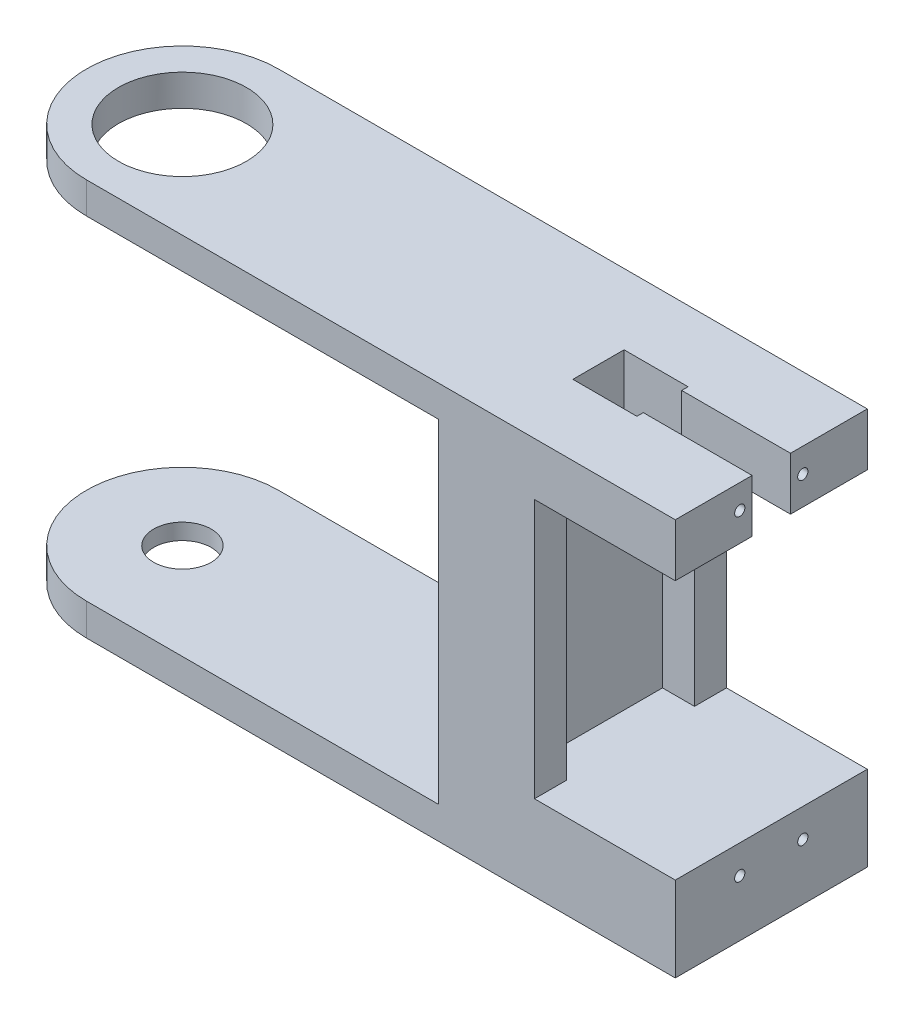
SolidWorks part; units mm, degrees
other "Marquage1"
sketch "Esquisse9" plane through (30.25, -27, 30) normal (0.9363, -0.2766, 0.2166) x (0.221, -0.0157, -0.9752)
sketch "Esquisse35" plane through (11.75, 27, 30) normal (0.9363, -0.2766, 0.2166) x (0.221, -0.0157, -0.9752)
ref_plane "Plan de face" through (0, 0, 0) normal (0, 0, 1) x (1, 0, 0)
ref_plane "Plan de dessus" through (0, 0, 0) normal (0, 1, 0) x (1, 0, 0)
ref_plane "Plan de droite" through (0, 0, 0) normal (1, 0, 0) x (0, 0, -1)
sketch "Esquisse1" plane through (0, 0, 0) normal (0, 0, 1) x (1, 0, 0)
  line L1 (-30.25, 32) -> (30.25, 32)
  line L2 (-30.25, 32) -> (-30.25, -32)
  line L3 (-30.25, -32) -> (30.25, -32)
  line L4 (30.25, 32) -> (30.25, -32)
  line L5 (-30.25, 32) -> (30.25, -32) construction
  line L6 (-30.25, -32) -> (30.25, 32) construction
  point P0 (0, 0)
  dimension "D1" = 60.5
  dimension "D2" = 64
extrude "Boss.-Extru.1" add sketch "Esquisse1" along normal blind 30
sketch "Esquisse2" plane through (30.25, 0, 0) normal (1, 0, 0) x (0, 0, -1)
  line L0 (-15, 32) -> (-15, -32) construction
  line L1 (-30, 32) -> (0, 32) construction
  line L2 (-30, -32) -> (0, -32) construction
  circle A0 centre (-15, -17) radius 4.5
  point P8 (-15, -17)
  dimension "D1" = 15
  dimension "D2" = 9
extrude "Enlèv. mat.-Extru.1" cut sketch "Esquisse2" against normal blind 32
sketch "Esquisse4" plane through (0, 0, 30) normal (0, 0, 1) x (1, 0, 0)
  line L0 (0, 0) -> (0, -11.7818) construction
  line L1 (-25.55, -56.5577) -> (25.55, -56.5577)
  line L2 (-25.55, -56.5577) -> (-25.55, 27)
  line L3 (-25.55, 27) -> (25.55, 27)
  line L4 (25.55, -56.5577) -> (25.55, 27)
  line L5 (30.25, 32) -> (-30.25, 32) construction
  dimension "D1" = 51.1
  dimension "D2" = 5
extrude "Enlèv. mat.-Extru.2" cut sketch "Esquisse4" against normal up to surface (30 mm away) up to face at (0, 0, 0)
sketch "Esquisse5" plane through (30.25, 0, 0) normal (1, 0, 0) x (0, 0, -1)
  circle A0 centre (-15, -17) radius 10.5
  dimension "D1" = 21
extrude "Enlèv. mat.-Extru.3" cut sketch "Esquisse5" against normal blind 2
sketch "Esquisse6" plane through (-25.55, 0, 0) normal (1, 0, 0) x (0, 0, -1)
  circle A0 centre (-15, -17) radius 10
extrude "Enlèv. mat.-Extru.4" cut sketch "Esquisse6" against normal up to surface (4.7 mm away) up to face at (-30.25, 0, 15)
sketch "Esquisse7" plane through (0, 0, 30) normal (0, 0, 1) x (1, 0, 0)
  line L0 (0, 0) -> (0, 32.5445) construction
  line L2 (-30.25, 32) -> (16.75, 32)
  line L3 (-30.25, 32) -> (-30.25, 89)
  line L4 (-30.25, 89) -> (16.75, 89)
  line L5 (16.75, 32) -> (16.75, 89)
  dimension "D1" = 57
  dimension "D2" = 47
extrude "Boss.-Extru.2" add sketch "Esquisse7" against normal up to surface (30 mm away) up to face at (0, -1.25, 0)
sketch "Esquisse8" plane through (0, 0, 30) normal (0, 0, 1) x (1, 0, 0)
  line L0 (-15.25, 90.392) -> (-15.25, 19.4965) construction
  line L1 (-30.25, 89) -> (-30.25, -32) construction
  line L2 (16.75, 60.5) -> (-55.9253, 60.5) construction
  line L3 (16.75, 32) -> (16.75, 89) construction
  line L4 (30.25, 32) -> (16.75, 32) construction
  line L6 (-15.25, 80.75) -> (11.75, 80.75)
  line L7 (-15.25, 80.75) -> (-15.25, 40.25)
  line L8 (-15.25, 40.25) -> (11.75, 40.25)
  line L10 (11.75, 40.25) -> (11.75, 32)
  line L11 (11.75, 101.1498) -> (21.75, 101.1498)
  line L12 (11.75, 101.1498) -> (11.75, 80.75)
  line L13 (11.75, 32) -> (21.75, 32)
  line L14 (21.75, 101.1498) -> (21.75, 32)
  dimension "D1" = 15
  dimension "D2" = 28.5
  dimension "D3" = 28.5
  dimension "D4" = 40.5
  dimension "D5" = 27
  dimension "D6" = 10
extrude "Enlèv. mat.-Extru.5" cut sketch "Esquisse8" against normal up to surface (30 mm away) up to face at (3.35, 16.8, 0)
sketch "Esquisse10" plane through (0, 80.75, 0) normal (0, -1, 0) x (1, 0, 0)
  line L0 (-1.75, 30) -> (-1.75, -1.0034) construction
  line L1 (-15.25, 15) -> (11.75, 15) construction
  line L2 (5.75, 0) -> (11.75, 0) construction
  line L4 (-15.25, 0) -> (11.75, 0)
  line L5 (11.75, 0) -> (11.75, 30)
  line L6 (11.75, 30) -> (-15.25, 30)
  line L7 (-15.25, 30) -> (-15.25, 0)
  line L8 (-15.25, 0) -> (-9.25, 0) construction
  line L9 (11.75, 0) -> (11.75, 30) construction
  line L10 (11.75, 30) -> (-15.25, 30) construction
  line L11 (-15.25, 30) -> (-15.25, 0) construction
  line L15 (-5.25, 11) -> (-5.25, 12)
  line L16 (-15.25, 19) -> (-5.25, 19)
  line L17 (-15.25, 19) -> (-15.25, 11)
  line L18 (-15.25, 11) -> (-5.25, 11)
  line L19 (34.75, 18) -> (34.75, 12)
  line L21 (-5.25, 19) -> (-5.25, 18)
  line L22 (-5.25, 18) -> (34.75, 18)
  line L24 (-5.25, 12) -> (34.75, 12)
  dimension "D2" = 6
  dimension "D4" = 10
  dimension "D1" = 0
extrude "Enlèv. mat.-Extru.6" cut sketch "Esquisse10" against normal up to surface (8.25 mm away) contours L17 L18 L15 L24 L19 L22 L21 L16 up to face at (-9.25, 89, 15)
sketch "Esquisse11" plane through (-15.25, 0, 0) normal (1, 0, 0) x (0, 0, -1)
  line L0 (-15, 103.0984) -> (-15, 64.9016) construction
  line L2 (0, 40.25) -> (-30, 40.25) construction
  line L3 (-30, 80.75) -> (-25, 80.75)
  line L4 (-30, 80.75) -> (-30, 40.25)
  line L5 (-30, 40.25) -> (-25, 40.25)
  line L6 (-25, 80.75) -> (-25, 40.25)
  line L7 (0, 40.25) -> (-5, 40.25)
  line L8 (-5, 80.75) -> (-5, 40.25)
  line L9 (0, 80.75) -> (-5, 80.75)
  line L10 (0, 80.75) -> (0, 40.25)
  point P3 (-15, 84)
  dimension "D1" = 5
extrude "Boss.-Extru.3" add sketch "Esquisse11" along normal blind 5
sketch "Esquisse12" plane through (11.75, 0, 0) normal (1, 0, 0) x (0, 0, -1)
  line L0 (-15, 89) -> (-15, 40.25) construction
  line L1 (-19, 89) -> (-11, 89) construction
  line L2 (0, 40.25) -> (-30, 40.25) construction
  line L3 (0, 80.75) -> (-12, 80.75) construction
  line L4 (-25, 60.5) -> (3.7732, 60.5) construction
  line L5 (-25, 40.25) -> (-25, 80.75) construction
  circle A0 centre (-19.925, 85.21) radius 0.5
  circle A1 centre (-10.075, 85.21) radius 0.5
  circle A2 centre (-10.075, 35.79) radius 0.5
  circle A3 centre (-19.925, 35.79) radius 0.5
  point P6 (-10.075, 85.21)
  point P9 (-19.925, 35.79)
  point P10 (-19.925, 85.21)
  point P15 (-10.075, 35.79)
  dimension "D3" = 1
  dimension "D1" = 4.46
  dimension "D2" = 4.925
  dimension "D4" = 4.925
  dimension "D5" = 4.46
extrude "Enlèv. mat.-Extru.7" cut sketch "Esquisse12" against normal blind 15
hole_wizard "Trou taraudé M2x0.42" positions "Esquisse3D2" profile "Esquisse14" tap size "M2x0.4" standard "Ansi Metric"
sketch3d "Esquisse3D2"
  line L0 (-3.25, 85.21, 19.925) -> (11.75, 85.21, 19.925) construction
  line L1 (-3.25, 85.21, 10.075) -> (11.75, 85.21, 10.075) construction
  line L2 (-3.25, 35.79, 10.075) -> (11.75, 35.79, 10.075) construction
  line L3 (-3.25, 35.79, 19.925) -> (11.75, 35.79, 19.925) construction
  point P0 (11.75, 85.21, 19.925)
  point P4 (11.75, 85.21, 10.075)
  point P8 (11.75, 35.79, 10.075)
  point P12 (11.75, 35.79, 19.925)
cosmetic thread "Filetage de perçage5" parameters "D1"=15, "D2"=2
cosmetic thread "Filetage de perçage6" parameters "D1"=15, "D2"=2
cosmetic thread "Filetage de perçage7" parameters "D1"=15, "D2"=2
cosmetic thread "Filetage de perçage8" parameters "D1"=15, "D2"=2
sketch "Esquisse14" plane through (11.75, 85.21, 19.925) normal (0, 1, 0) x (0, 0, -1)
  line L0 (0, 0) -> (0, 17.4807)
  line L1 (0, 17.4807) -> (0.8, 17)
  line L2 (0.8, 17) -> (0.8, 0)
  line L5 (0.8, 0) -> (0, 0)
  line L10 (0, 17.4807) -> (-0.8, 17) construction
  line L11 (0, -6.35) -> (0, 107.95) construction
  dimension "Diamètre du trou pour taraudage" = 1.6
  dimension "Profondeur du trou pour taraudage" = 17
  dimension "Angle de pointe" = 118
sketch "Esquisse15" plane through (-30.25, 0, 0) normal (-1, 0, 0) x (0, 0, 1)
  line L0 (30, -32) -> (0, -32) construction
  line L1 (40, -17) -> (30, -17)
  line L2 (0, -17) -> (-10, -17)
  arc A0 (5, -17) -> (25, -17) centre (15, -17) ccw construction
  arc A1 (0, -17) -> (30, -17) centre (15, -17) ccw
  arc A2 (-10, -17) -> (40, -17) centre (15, -17) ccw
  dimension "D1" = 20
  dimension "D2" = 50
extrude "Enlèv. mat.-Extru.8" cut sketch "Esquisse15" against normal up to surface (60.5 mm away) up to face at (30.25, -6.5, 15)
sketch "Esquisse17" plane through (-15.25, 0, 0) normal (1, 0, 0) x (0, 0, -1)
  line L0 (-15, 89) -> (-15, 40.25) construction
  line L1 (-19, 89) -> (-11, 89) construction
  line L2 (0, 40.25) -> (-30, 40.25) construction
  line L3 (-5, 70.15) -> (-34.9076, 70.15) construction
  line L4 (-5, 80.75) -> (-5, 40.25) construction
  line L5 (-25, 40.25) -> (-25, 80.75) construction
  line L6 (-5, 40.25) -> (-25, 40.25) construction
  circle A0 centre (-15, 70.15) radius 9.25
  point P14 (-15, 70.15)
  dimension "D1" = 10
  dimension "D2" = 29.9
sketch "Esquisse21" plane through (-30.25, 0, 0) normal (-1, 0, 0) x (0, 0, 1)
  circle A0 centre (15, 70.15) radius 9.25 construction
  circle A1 centre (15, 70.15) radius 9.25 construction
  circle A2 centre (15, 70.15) radius 1
  point P4 (15, 70.15)
sketch "Esquisse22" plane through (0, 0, 30) normal (0, 0, 1) x (1, 0, 0)
  line L0 (25.55, 27) -> (-25.55, 27) construction
  line L1 (39.5686, -40.8758) -> (-43.4034, -40.8758)
  line L2 (39.5686, -40.8758) -> (39.5686, 27)
  line L3 (39.5686, 27) -> (-43.4034, 27)
  line L4 (-43.4034, -40.8758) -> (-43.4034, 27)
extrude "Enlèv. mat.-Extru.10" cut sketch "Esquisse22" against normal up to surface (30 mm away) up to face at (1.8929, 33.5714, 0)
sketch "Esquisse23" plane through (0, 0, 0) normal (0, 0, -1) x (-1, 0, 0)
  line L0 (30.25, 58) -> (46.9038, 58) construction
  line L1 (30.25, 89) -> (30.25, 27) construction
  line L2 (30.25, 32) -> (85.25, 32)
  line L3 (30.25, 89) -> (85.25, 89)
  line L4 (30.25, 89) -> (30.25, 84.1)
  line L5 (30.25, 84.1) -> (85.25, 84.1)
  line L6 (85.25, 89) -> (85.25, 84.1)
  line L7 (85.25, 27) -> (85.25, 32)
  line L8 (30.25, 27) -> (85.25, 27)
  line L9 (30.25, 27) -> (30.25, 32)
  line L10 (30.25, 27) -> (-30.25, 27) construction
  dimension "D1" = 4.9
  dimension "D2" = 55
  dimension "D3" = 5
  dimension "D4" = 52.1
extrude "Boss.-Extru.4" add sketch "Esquisse23" against normal up to surface (30 mm away) up to face at (2.65, 53.8, 30)
sketch "Esquisse24" plane through (0, 27, 0) normal (0, -1, 0) x (1, 0, 0)
  line L0 (-85.25, 15) -> (-94.2291, 15) construction
  line L2 (-74.25, 35) -> (-74.25, -10.9716) construction
  line L3 (-30.25, 30) -> (-30.25, 0) construction
  line L4 (-30.25, 30) -> (-30.25, 0)
  circle A0 centre (-74.25, 15) radius 10
  dimension "D1" = 20
  dimension "D2" = 44
extrude "Enlèv. mat.-Extru.11" cut sketch "Esquisse24" against normal up to surface (62 mm away) contours A0
sketch "Esquisse25" plane through (0, 27, 0) normal (0, -1, 0) x (1, 0, 0)
  line L0 (30.25, 30) -> (-85.25, 30) construction
  line L1 (-85.25, 0) -> (30.25, 0) construction
  line L2 (-74.25, 44.1348) -> (-74.25, 30)
  line L3 (-74.25, 0) -> (-74.25, -14.1348)
  arc A0 (-74.25, 30) -> (-74.25, 0) centre (-74.25, 15) ccw
  arc A1 (-74.25, 44.1348) -> (-74.25, -14.1348) centre (-74.25, 15) ccw
extrude "Enlèv. mat.-Extru.12" cut sketch "Esquisse25" against normal up to surface (62 mm away) up to face at (-74.25, 89, 25)
sketch "Esquisse26" plane through (0, 27, 0) normal (0, -1, 0) x (1, 0, 0)
  circle A0 centre (-74.25, 15) radius 4.5
  circle A1 centre (-74.25, 15) radius 10.5
extrude "Boss.-Extru.5" add sketch "Esquisse26" against normal up to surface (5 mm away) up to face at (-74.25, 32, 25)
sketch "Esquisse27" plane through (0, 27, 0) normal (0, -1, 0) x (1, 0, 0)
  circle A0 centre (-74.25, 15) radius 10.5
extrude "Enlèv. mat.-Extru.13" cut sketch "Esquisse27" against normal offset from surface (2.5 mm away) 2.5 up to face at (-63.4171, 32, 15)
sketch "Esquisse28" plane through (0, 32, 0) normal (0, 1, 0) x (1, 0, 0)
  line L1 (11.75, 0) -> (33.2878, 0)
  line L2 (11.75, 0) -> (11.75, -33.2244)
  line L3 (11.75, -33.2244) -> (33.2878, -33.2244)
  line L4 (33.2878, 0) -> (33.2878, -33.2244)
extrude "Enlèv. mat.-Extru.14" cut sketch "Esquisse28" against normal up to surface (5 mm away) up to face at (-63.75, 27, 15)
sketch "Esquisse29" plane through (0, 0, 0) normal (0, 0, -1) x (-1, 0, 0)
  line L0 (74.25, 32) -> (30.25, 32) construction
  line L1 (30.25, 84.1) -> (25.25, 84.1)
  line L2 (30.25, 84.1) -> (30.25, 32)
  line L3 (30.25, 32) -> (25.25, 32)
  line L4 (25.25, 84.1) -> (25.25, 32)
  dimension "D1" = 5
extrude "Enlèv. mat.-Extru.15" cut sketch "Esquisse29" against normal up to surface (30 mm away) up to face at (-27.5833, 58.85, 30)
sketch "Esquisse31" plane through (0, 27, 0) normal (0, -1, 0) x (1, 0, 0)
  line L0 (-82.4117, 21.6059) -> (-85.25, 25.198)
  line L1 (-74.25, 4.5) -> (-85.25, 4.802)
  arc A0 (-85.25, 25.198) -> (-85.25, 4.802) centre (-74.25, 15) ccw
  arc A1 (-85.25, 4.802) -> (-74.25, 0) centre (-74.25, 15) ccw construction
  arc A2 (-82.4117, 21.6059) -> (-74.25, 4.5) centre (-74.25, 15) ccw
  circle A3 centre (-74.25, 15) radius 10.5 construction
  circle M1 centre (-74.25, 15) radius 10.5
  line M6 (-85.25, 25.198) -> (-85.25, 4.802)
extrude "Boss.-Extru.6" add sketch "Esquisse31" against normal up to surface (62 mm away) contours L1 L0 M1 M6 | A0 M6 up to face at (-74.25, 89, 25)
sketch "Esquisse32" plane through (0.0675, 0, 2.4599) normal (-0.0274, 0, -0.9996) x (-0.9996, 0, 0.0274)
  line L0 (85.3497, 32) -> (74.222, 32) construction
  line L1 (74.9218, 84.1) -> (113.711, 84.1)
  line L2 (74.9218, 84.1) -> (74.9218, 32)
  line L3 (74.9218, 32) -> (113.711, 32)
  line L4 (113.711, 84.1) -> (113.711, 32)
extrude "Enlèv. mat.-Extru.16" cut sketch "Esquisse32" against normal up to surface (24.429 mm away)
sketch "Esquisse33" plane through (0, 32, 0) normal (0, 1, 0) x (1, 0, 0)
  line L3 (-74.25, -30) -> (-25.25, -30)
  line L4 (-25.25, -30) -> (-25.25, 0)
  line L5 (-25.25, 0) -> (-74.25, 0)
  line L6 (-74.25, -30) -> (-25.25, -30)
  line L7 (-25.25, -30) -> (-25.25, 0)
  line L8 (-25.25, 0) -> (-74.25, 0)
  arc A1 (-74.25, 0) -> (-74.25, -30) centre (-74.25, -15) ccw
  arc A2 (-74.25, 0) -> (-74.25, -30) centre (-74.25, -15) ccw
  dimension "D1" = 0
extrude "Boss.-Extru.7" [suppressed] add sketch "Esquisse33" along normal blind 0.4
sketch "Esquisse34" [suppressed] plane through (0, 32, 0) normal (0, -1, 0) x (1, 0, 0)
  circle A0 centre (-74.25, 15) radius 4.5
extrude "Enlèv. mat.-Extru.17" [suppressed] cut sketch "Esquisse34" against normal up to surface (0.4 mm away)
sketch "Esquisse36" plane through (0, 27, 0) normal (0, -1, 0) x (1, 0, 0)
  line L3 (-96.1298, 39.4832) -> (-25.25, 39.4832)
  line L4 (-96.1298, 39.4832) -> (-96.1298, -4.8162)
  line L5 (-96.1298, -4.8162) -> (-25.25, -4.8162)
  line L6 (-25.25, 39.4832) -> (-25.25, -4.8162)
extrude "Enlèv. mat.-Extru.20" cut sketch "Esquisse36" against normal up to surface (62 mm away) contours L4 L3 L6 L5 up to face at (-14, 89, 15)
sketch "Esquisse37" plane through (-25.25, 0, 0) normal (-1, 0, 0) x (0, 0, 1)
  line L0 (30, 89) -> (30, 27) construction
  line L1 (0, 89) -> (30, 89)
  line L2 (0, 89) -> (0, 84.1)
  line L3 (0, 84.1) -> (30, 84.1)
  line L4 (30, 89) -> (30, 84.1)
  line L6 (0, 27) -> (30, 27)
  line L7 (0, 27) -> (0, 32)
  line L8 (0, 32) -> (30, 32)
  line L9 (30, 27) -> (30, 32)
  dimension "D1" = 4.9
  dimension "D2" = 5
  dimension "D3" = 52.1
extrude "Boss.-Extru.8" add sketch "Esquisse37" along normal blind 70
sketch "Esquisse38" plane through (0, 27, 0) normal (0, -1, 0) x (1, 0, 0)
  line L0 (-95.25, 15) -> (-54.6175, 15) construction
  line L1 (-95.25, 0) -> (-95.25, 30) construction
  circle A0 centre (-80.25, 15) radius 4.5
  dimension "D1" = 15
extrude "Enlèv. mat.-Extru.21" cut sketch "Esquisse38" against normal up to surface (62 mm away) up to face at (-16.25, 89, 15)
sketch "Esquisse39" plane through (0, 89, 0) normal (0, 1, 0) x (1, 0, 0)
  circle A0 centre (-80.25, -15) radius 10
extrude "Enlèv. mat.-Extru.22" cut sketch "Esquisse39" against normal up to surface (4.9 mm away) up to face at (-84.75, 84.1, 15)
sketch "Esquisse40" plane through (0, 27, 0) normal (0, -1, 0) x (1, 0, 0)
  circle A0 centre (-80.25, 15) radius 10.5
extrude "Enlèv. mat.-Extru.23" cut sketch "Esquisse40" against normal offset from surface (2.5 mm away) 2.5 up to face at (-75.75, 32, 15)
sketch "Esquisse42" plane through (0, 27, 0) normal (0, -1, 0) x (1, 0, 0)
  line L0 (11.75, 30) -> (-95.25, 30) construction
  line L1 (-95.25, 0) -> (11.75, 0) construction
  line L2 (-80.25, 38.9229) -> (-80.25, 30)
  line L3 (-80.25, 0) -> (-80.25, -8.9229)
  arc A0 (-80.25, 30) -> (-80.25, 0) centre (-80.25, 15) ccw
  arc A1 (-80.25, 38.9229) -> (-80.25, -8.9229) centre (-80.25, 15) ccw
  point P10 (0, 0)
  point P11 (0, 0)
  dimension "D1" = 15
extrude "Enlèv. mat.-Extru.24" cut sketch "Esquisse42" against normal up to surface (62 mm away) up to face at (-80.25, 89, 25)
